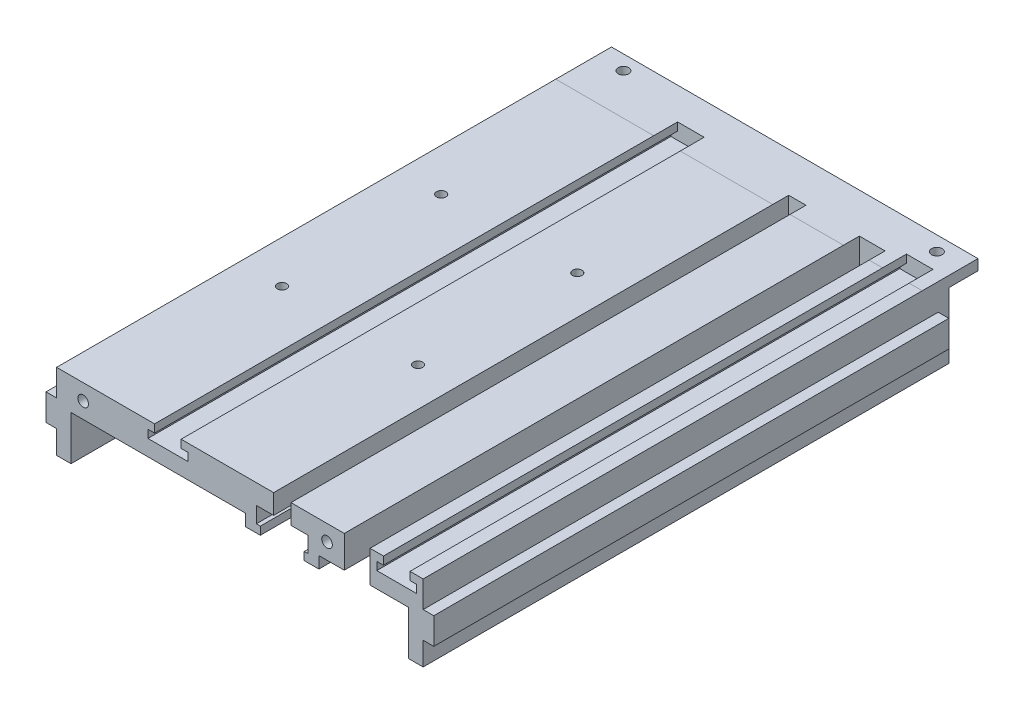
SolidWorks part; units mm, degrees
ref_plane "Alzado" through (0, 0, 0) normal (0, 0, 1) x (1, 0, 0)
ref_plane "Planta" through (0, 0, 0) normal (0, 1, 0) x (1, 0, 0)
ref_plane "Vista lateral" through (0, 0, 0) normal (1, 0, 0) x (0, 0, -1)
sketch "Croquis1" plane through (0, 0, 0) normal (0, 0, 1) x (1, 0, 0)
  line L1 (-85, 25) -> (85, 25)
  line L2 (-85, 25) -> (-85, -25)
  line L3 (-85, -25) -> (85, -25)
  line L4 (85, 25) -> (85, -25)
  line L5 (-85, 25) -> (85, -25) construction
  line L6 (-85, -25) -> (85, 25) construction
  point P0 (0, 0)
  dimension "D1" = 170
  dimension "D2" = 50
extrude "Saliente-Extruir1" add sketch "Croquis1" along normal blind 4
sketch "Croquis3" plane through (0, 0, 4) normal (0, 0, 1) x (1, 0, 0)
  line L0 (0, -17.5197) -> (0, -3.6911) construction
  line L4 (-13.7721, -12.6911) -> (-9.7721, -12.6911)
  line L7 (-85, -8.2699) -> (-13.7721, -8.2699)
  line L8 (85, 25) -> (-85, 25) construction
  line L9 (0, 3.7401) -> (0, 25) construction
  line L10 (-9.7721, -3.6911) -> (-9.7721, -9.6911)
  line L11 (-85, 25) -> (-85, -25) construction
  line L13 (-13.7721, -8.2699) -> (-13.7721, -12.6911)
  line L17 (13.7721, -12.6911) -> (13.7721, -8.2699)
  line L22 (9.7721, -12.6911) -> (13.7721, -12.6911)
  line L29 (13.7721, -8.2699) -> (23.3572, -8.2699) construction
  line L31 (-9.7721, -9.6911) -> (-8.2721, -9.6911)
  line L32 (-8.2721, -9.6911) -> (-8.2721, -12.6911)
  line L33 (-8.2721, -12.6911) -> (-9.7721, -12.6911)
  line L34 (9.7721, -9.6911) -> (8.2721, -9.6911)
  line L35 (8.2721, -9.6911) -> (8.2721, -12.6911)
  line L36 (8.2721, -12.6911) -> (9.7721, -12.6911)
  line L49 (-9.7721, -3.6911) -> (9.7721, -3.6911)
  line L55 (9.7721, -3.6911) -> (9.7721, -9.6911)
  line L60 (23.3572, -8.2699) -> (23.3572, 3.7401)
  line L61 (13.7721, -8.2699) -> (23.3572, -8.2699)
  line L62 (-85, 3.7401) -> (23.3572, 3.7401)
  line L66 (-85, 3.7401) -> (-85, -8.2699)
  line L67 (43.0537, -8.2699) -> (42.4285, 3.7401) construction
  line L72 (23.3572, 3.7401) -> (43.0537, 3.7401) construction
  line L77 (33.0537, 3.7401) -> (53.0537, 3.7401)
  line L78 (33.0537, 3.7401) -> (33.0537, -8.2699)
  line L79 (33.0537, -8.2699) -> (53.0537, -8.2699)
  line L80 (53.0537, 3.7401) -> (53.0537, -8.2699)
  line L81 (42.4285, 3.7401) -> (42.4285, -8.2699) construction
  line L82 (42.4285, -8.2699) -> (43.73, -10.4481) construction
  line L83 (43.73, -10.4481) -> (43.1048, -10.4481) construction
  line L84 (43.1048, -8.8827) -> (43.1048, -10.4481) construction
  line L85 (43.0537, -8.2699) -> (43.1048, -8.8827) construction
  point P4 (43.0537, 3.7401)
  point P50 (0, -17.5197)
  dimension "D1" = 4
  dimension "D2" = 3
  dimension "D3" = 6
  dimension "D4" = 1.5
  dimension "D5" = 12.01
  dimension "D6" = 20
  dimension "D7" = 92.98
  dimension "D8" = 21.2599
  dimension "D9" = 12.01
extrude "Saliente-Extruir2" add sketch "Croquis3" along normal blind 194
sketch "Croquis22" plane through (0, 0, 0) normal (0, 0, -1) x (-1, 0, 0)
  line L0 (85, 25) -> (85, -25) construction
  line L1 (-85, 25) -> (85, 25)
  line L2 (-85, 25) -> (-85, 3.74)
  line L3 (-85, 3.74) -> (85, 3.74)
  line L4 (85, 25) -> (85, 3.74)
  dimension "D1" = 21.26
extrude "Cortar-Extruir12" cut sketch "Croquis22" against normal blind 10
sketch "Croquis23" plane through (0, 0, 0) normal (0, 0, -1) x (-1, 0, 0)
  line L0 (85, 3.74) -> (85, -25) construction
  line L1 (-85, 3.74) -> (85, 3.74)
  line L2 (-85, 3.74) -> (-85, -4.3828)
  line L3 (-85, -4.3828) -> (85, -4.3828)
  line L4 (85, 3.74) -> (85, -4.3828)
extrude "Saliente-Extruir6" add sketch "Croquis23" along normal blind 11
sketch "Croquis25" plane through (0, -3.6911, 0) normal (0, -1, 0) x (1, 0, 0)
  line L13 (-9.7721, 198) -> (9.7721, 198) construction
  line L15 (-3.2574, 198) -> (3.2574, 198)
  line L16 (-3.2574, 198) -> (-3.2574, 4)
  line L17 (-3.2574, 4) -> (3.2574, 4)
  line L19 (3.2574, 198) -> (3.2574, 4)
  line L20 (-9.7721, 4) -> (9.7721, 4) construction
  line L21 (-9.7721, 194.1828) -> (-3.2574, 194.1828) construction
  line L22 (-9.7721, 198) -> (-9.7721, 4) construction
  line L23 (-3.2574, 194.1828) -> (3.2574, 194.1828) construction
  line L24 (3.2574, 194.1828) -> (9.7721, 194.1828) construction
  line L25 (9.7721, 198) -> (9.7721, 4) construction
extrude "Cortar-Extruir16" cut sketch "Croquis25" against normal blind 10
sketch "Croquis27" plane through (0, -8.2699, 0) normal (0, -1, 0) x (1, 0, 0)
  line L0 (-69.0121, 129.1176) -> (-17.7721, 129.1176) construction
  line L1 (-17.7721, 129.1176) -> (-17.7721, 69.1176) construction
  line L2 (-17.7721, 69.1176) -> (-69.0121, 69.1176) construction
  line L3 (-17.7721, 129.1176) -> (-16.0221, 129.1176) construction
  line L4 (-31.3046, 147.8049) -> (-17.7721, 129.1176) construction
  line L5 (-69.0121, 129.1176) -> (-85, 129.1176) construction
  line L6 (-85, 198) -> (-85, 4) construction
  line L7 (-85, 129.1176) -> (-31.3046, 147.8049) construction
  line L8 (-17.7721, 129.1176) -> (-16.0221, 129.1176) construction
  line L10 (-17.7721, 129.1176) -> (-13.7721, 129.1176) construction
  line L11 (-13.7721, 198) -> (-13.7721, 4) construction
  circle A0 centre (-69.0121, 129.1176) radius 1.75
  circle A1 centre (-17.7721, 129.1176) radius 1.75
  circle A2 centre (-69.0121, 69.1176) radius 1.75
  circle A3 centre (-17.7721, 69.1176) radius 1.75
  dimension "D1" = 3.5
  dimension "D3" = 51.24
  dimension "D2" = 60
  dimension "D4" = 4
extrude "Cortar-Extruir17" cut sketch "Croquis27" against normal blind 30.74
sketch "Croquis28" plane through (0, 0, 198) normal (0, 0, 1) x (1, 0, 0)
  line L0 (-85, 3.7401) -> (-45, 3.7401) construction
  line L1 (50.605, 0.7401) -> (50.605, -2.2599)
  line L2 (50.605, -2.2599) -> (35.605, -2.2599)
  line L4 (-3.2574, 3.7401) -> (-85, 3.7401) construction
  line L6 (-48.105, 0.7401) -> (-50.605, 0.7401) construction
  line L7 (-38.105, 3.7401) -> (-48.105, 3.7401)
  line L8 (-38.105, 3.7401) -> (-38.105, 0.7401)
  line L10 (-48.105, 3.7401) -> (-48.105, 0.7401)
  line L11 (-50.605, 0.7401) -> (-48.105, 0.7401)
  line L12 (-50.605, 0.7401) -> (-50.605, -2.2599)
  line L13 (-50.605, -2.2599) -> (-35.605, -2.2599)
  line L14 (-35.605, 0.7401) -> (-35.605, -2.2599)
  line L15 (-38.105, 0.7401) -> (-35.605, 0.7401) construction
  line L16 (-38.105, 0.7401) -> (-35.605, 0.7401)
  line L17 (35.605, 0.7401) -> (35.605, -2.2599)
  line L18 (38.105, 0.7401) -> (35.605, 0.7401)
  line L34 (-85, 3.7401) -> (-85, -8.2699) construction
  line L35 (38.105, 3.7401) -> (38.105, 0.7401)
  line L36 (0, 0) -> (0, 3.7401) construction
  line L37 (38.105, 3.7401) -> (48.105, 3.7401)
  line L40 (48.105, 3.7401) -> (48.105, 0.7401)
  line L41 (50.605, 0.7401) -> (48.105, 0.7401)
  point P25 (-43.105, -2.2599)
  dimension "D1" = 41.895
  dimension "D2" = 10
  dimension "D3" = 15
  dimension "D4" = 3
  dimension "D5" = 3
extrude "Cortar-Extruir18" cut sketch "Croquis28" against normal blind 197
sketch "Croquis29" plane through (0, 0, 4) normal (0, 0, 1) x (1, 0, 0)
  line L9 (53.0537, 3.7401) -> (85, 3.7401)
  line L10 (53.0537, 3.7401) -> (53.0537, -25)
  line L11 (53.0537, -25) -> (85, -25)
  line L12 (85, 3.7401) -> (85, -25)
extrude "Cortar-Extruir19" cut sketch "Croquis29" against normal blind 197
sketch "Croquis30" plane through (0, 0, 4) normal (0, 0, 1) x (1, 0, 0)
  line L0 (-85, -16.6349) -> (53.0537, -16.6349) construction
  line L1 (-85, -8.2699) -> (-85, -25) construction
  line L2 (53.0537, -8.2699) -> (53.0537, -25) construction
  line L3 (-15.9731, -25) -> (-15.9731, -8.2699) construction
  line L4 (-85, -25) -> (53.0537, -25) construction
  line L5 (-85, -8.2699) -> (-13.7721, -8.2699) construction
  circle A0 centre (-72, -16.6349) radius 2
  circle A1 centre (40.0537, -16.6349) radius 2
  dimension "D2" = 4
  dimension "D1" = 13
extrude "Cortar-Extruir20" cut sketch "Croquis30" against normal blind 197
sketch "Croquis31" plane through (0, 0, 198) normal (0, 0, 1) x (1, 0, 0)
  line L0 (-85, -2.2649) -> (23.3572, -2.2649) construction
  line L1 (-85, 3.7401) -> (-85, -8.2699) construction
  line L2 (23.3572, -8.2699) -> (23.3572, 3.7401) construction
  circle A0 centre (-75, -2.2649) radius 2
  circle A1 centre (16.8572, -2.2649) radius 2
  dimension "D1" = 4
  dimension "D2" = 10
  dimension "D3" = 6.5
extrude "Unión techo" cut sketch "Croquis31" against normal blind 10
sketch "Croquis33" plane through (0, -4.3828, 0) normal (0, -1, 0) x (1, 0, 0)
  line L0 (-85, -5.5) -> (53.0537, -5.5) construction
  line L1 (-85, -11) -> (-85, 0) construction
  line L2 (53.0537, -11) -> (53.0537, 0) construction
  circle A0 centre (-75, -5.5) radius 2
  circle A1 centre (43.0537, -5.5) radius 2
  dimension "D1" = 4
  dimension "D2" = 4
  dimension "D3" = 10
  dimension "D4" = 10
extrude "Cortar-Extruir22" cut sketch "Croquis33" against normal blind 10
sketch "Croquis35" plane through (0, -4.3828, 0) normal (0, -1, 0) x (1, 0, 0)
  line L1 (-85, -11) -> (53.0537, -11)
  line L2 (-85, -11) -> (-85, 0)
  line L3 (-85, 0) -> (53.0537, 0)
  line L4 (53.0537, -11) -> (53.0537, 0)
extrude "Cortar-Extruir24" cut sketch "Croquis35" against normal blind 4.12
sketch "Croquis36" plane through (0, 0, 4) normal (0, 0, 1) x (1, 0, 0)
  line L0 (-85, -25) -> (53.0537, -25) construction
  line L1 (-85, -8.2699) -> (-79.5814, -8.2699)
  line L2 (-85, -16.2599) -> (-85, -25)
  line L3 (-85, -25) -> (-79.5814, -25)
  line L4 (-79.5814, -8.2699) -> (-79.5814, -25)
  line L5 (-85, -6.2599) -> (-89, -6.2599)
  line L6 (-85, 3.7401) -> (-85, -8.2699) construction
  line L7 (-89, -6.2599) -> (-89, -16.2599)
  line L8 (-89, -16.2599) -> (-85, -16.2599)
  line L9 (-85, -8.2699) -> (-85, -6.2599)
  line L10 (-48.105, 3.7401) -> (-85, 3.7401) construction
  line L11 (-15.9731, -25) -> (-15.9731, 3.734) construction
  line L13 (53.0537, -8.2699) -> (53.0537, -6.2599)
  line L14 (53.0537, -6.2599) -> (57.0537, -6.2599)
  line L15 (57.0537, -6.2599) -> (57.0537, -16.2599)
  line L16 (57.0537, -16.2599) -> (53.0537, -16.2599)
  line L17 (53.0537, -16.2599) -> (53.0537, -25)
  line L18 (53.0537, -25) -> (47.6351, -25)
  line L19 (47.6351, -8.2699) -> (47.6351, -25)
  line L20 (53.0537, -8.2699) -> (47.6351, -8.2699)
  dimension "D1" = 10
  dimension "D2" = 10
  dimension "D3" = 4
extrude "Saliente-Extruir7" add sketch "Croquis36" along normal blind 194
